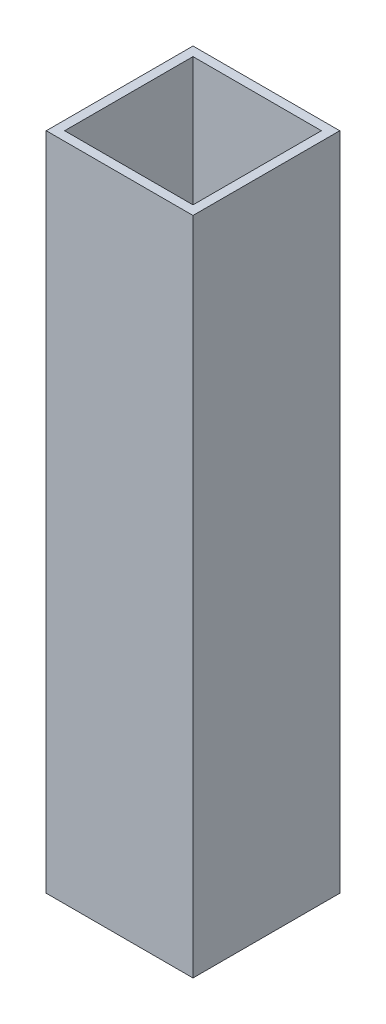
SolidWorks part; units mm, degrees
material "6061 Alloy"
ref_plane "Front Plane" through (0, 0, 0) normal (0, 0, 1) x (1, 0, 0)
ref_plane "Top Plane" through (0, 0, 0) normal (0, 1, 0) x (1, 0, 0)
ref_plane "Right Plane" through (0, 0, 0) normal (1, 0, 0) x (0, 0, -1)
sketch "Sketch1" plane through (0, 0, 0) normal (0, 1, 0) x (1, 0, 0)
  line L1 (-12.7, -12.7) -> (12.7, -12.7)
  line L2 (-12.7, -12.7) -> (-12.7, 12.7)
  line L3 (-12.7, 12.7) -> (12.7, 12.7)
  line L4 (12.7, -12.7) -> (12.7, 12.7)
  line L7 (-11.1125, -11.1125) -> (11.1125, -11.1125)
  line L8 (-11.1125, -11.1125) -> (-11.1125, 11.1125)
  line L9 (-11.1125, 11.1125) -> (11.1125, 11.1125)
  line L10 (11.1125, -11.1125) -> (11.1125, 11.1125)
  point P6 (0, 0)
  dimension "D1" = 25.4
  dimension "D2" = 25.4
  dimension "D3" = 1.5875
  dimension "D4" = 1.5875
  dimension "D5" = 1.5875
extrude "Boss-Extrude1" add sketch "Sketch1" along normal blind 114.3
